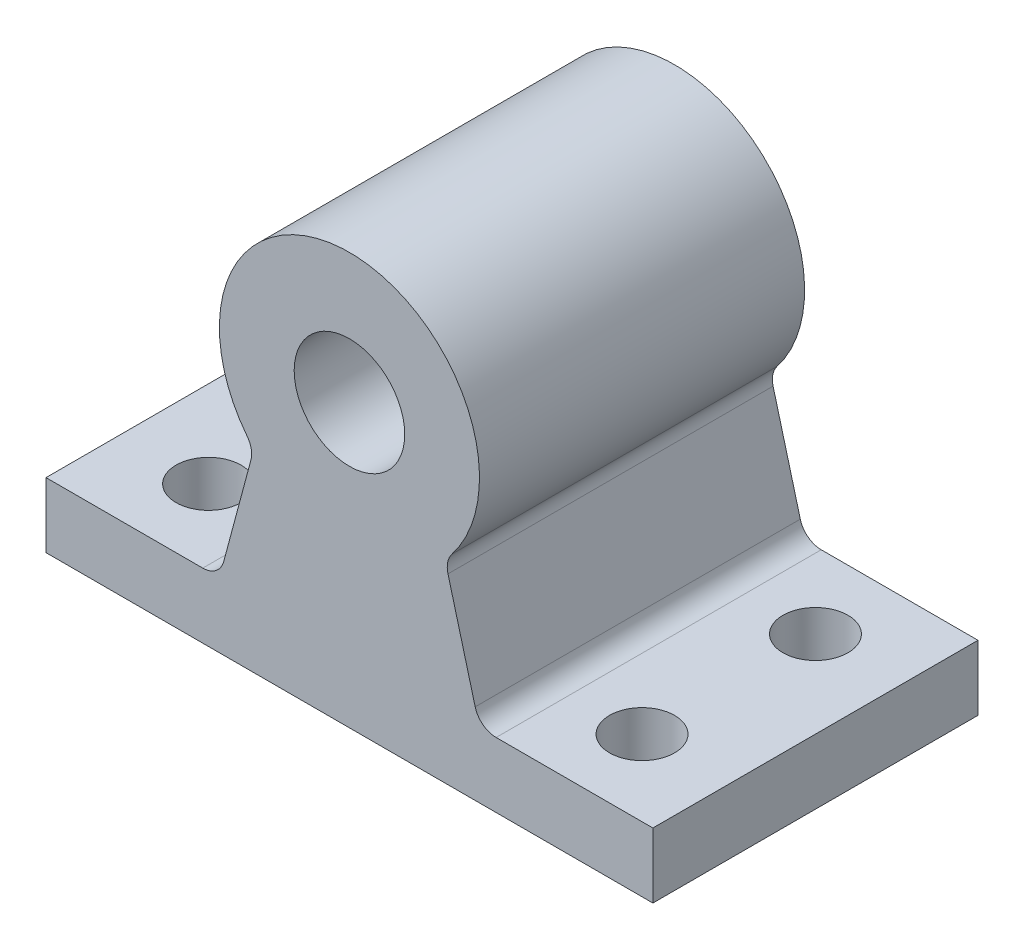
SolidWorks part; units mm, degrees
material "POM 乙缩醛共聚物"
ref_plane "前视基准面" through (0, 0, 0) normal (0, 0, 1) x (1, 0, 0)
ref_plane "上视基准面" through (0, 0, 0) normal (0, 1, 0) x (1, 0, 0)
ref_plane "右视基准面" through (0, 0, 0) normal (1, 0, 0) x (0, 0, -1)
sketch "草图1" plane through (0, 0, 0) normal (0, 0, 1) x (1, 0, 0)
  line L0 (-15.6056, 0) -> (19.1143, 0) construction
  line L1 (0, 16.5221) -> (0, -13.5371) construction
  line L2 (-4.4105, 8.9321) -> (-6, 3)
  line L3 (-6, 3) -> (-14, 3)
  line L4 (-14, 3) -> (-14, 0)
  line L5 (-14, 0) -> (14, 0)
  line L6 (4.4105, 8.9321) -> (6, 3)
  line L7 (6, 3) -> (14, 3)
  line L8 (14, 3) -> (14, 0)
  circle A0 centre (0, 13) radius 2.55
  circle A1 centre (0, 13) radius 6
  point P17 (0, 0)
  dimension "D1" = 5.1
  dimension "D3" = 12
  dimension "D2" = 13
  dimension "D4" = 3
  dimension "D5" = 28
  dimension "D6" = 75
  dimension "D7" = 12
extrude "凸台-拉伸1" add sketch "草图1" along normal mid plane 15 contours A1 A0 | A1 L2 L3 L4 L5 L8 L7 L6
sketch "草图2" plane through (0, 0, 0) normal (0, -1, 0) x (1, 0, 0)
  line L0 (0, 7.5) -> (0, -9.4155) construction
  line L1 (-14, 7.5) -> (14, 7.5) construction
  line L2 (-17.3945, 0) -> (19.575, 0) construction
  circle A0 centre (-10, 4) radius 1.5
  circle A1 centre (-10, -4) radius 1.5
  circle A2 centre (10, -4) radius 1.5
  circle A3 centre (10, 4) radius 1.5
  dimension "D1" = 3
  dimension "D2" = 20
  dimension "D3" = 8
extrude "切除-拉伸1" cut sketch "草图2" against normal through all
sketch "草图3" plane through (0, 0, -7.5) normal (0, 0, -1) x (-1, 0, 0)
  line L1 (0, 8.1503) -> (4.2, 10.5751)
  line L2 (4.2, 10.5751) -> (4.2, 15.4249)
  line L3 (4.2, 15.4249) -> (0, 17.8497)
  line L4 (0, 17.8497) -> (-4.2, 15.4249)
  line L5 (-4.2, 15.4249) -> (-4.2, 10.5751)
  line L6 (-4.2, 10.5751) -> (0, 8.1503)
  circle A0 centre (0, 13) radius 2.55 construction
  circle A1 centre (0, 13) radius 2.55 construction
  circle A2 centre (0, 13) radius 4.2 construction
  dimension "D1" = 8.4
extrude "切除-拉伸2" cut sketch "草图3" against normal blind 9.5
fillet "圆角1" radius 1 10 edges at (4.4105, 8.9321, 0) (-4.4105, 8.9321, 0) (-6, 3, 0) (6, 3, 0) (4.2, 10.5751, -2.75) (4.2, 15.4249, -2.75) (-4.2, 15.4249, -2.75) (-4.2, 10.5751, -2.75) (0, 8.1503, -2.75) (0, 17.8497, -2.75)
